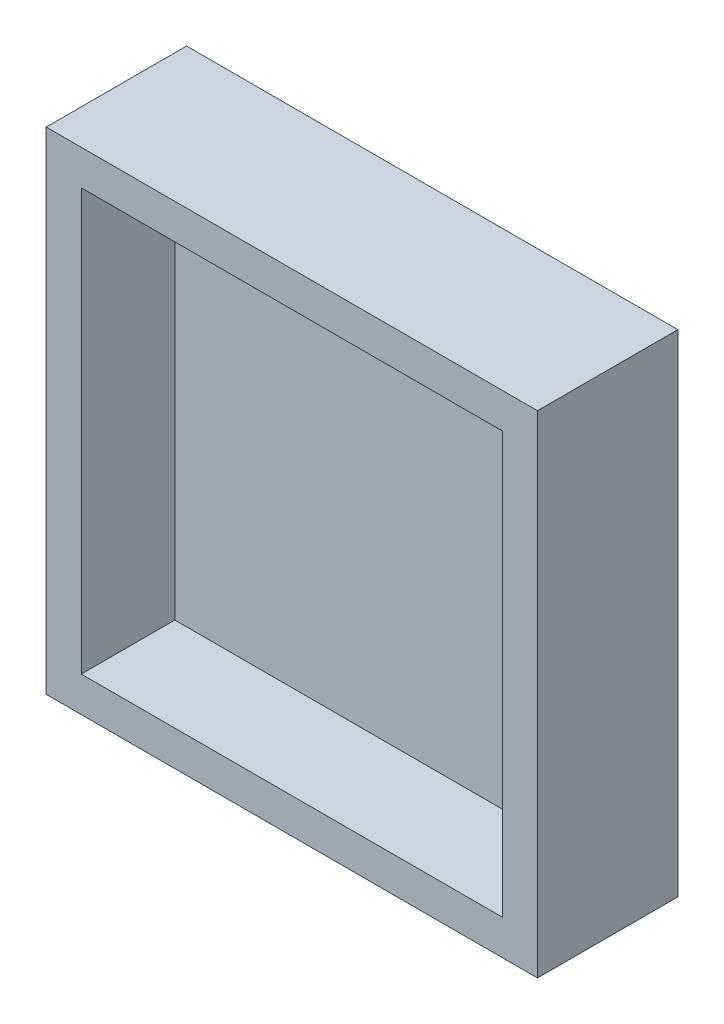
SolidWorks part; units mm, degrees
ref_plane "Front Plane" through (0, 0, 0) normal (0, 0, 1) x (1, 0, 0)
ref_plane "Top Plane" through (0, 0, 0) normal (0, 1, 0) x (1, 0, 0)
ref_plane "Right Plane" through (0, 0, 0) normal (1, 0, 0) x (0, 0, -1)
sketch "Sketch1" plane through (0, 0, 0) normal (0, 0, 1) x (1, 0, 0)
  line L1 (-66.675, -66.675) -> (66.675, -66.675)
  line L2 (-66.675, -66.675) -> (-66.675, 66.675)
  line L3 (-66.675, 66.675) -> (66.675, 66.675)
  line L4 (66.675, -66.675) -> (66.675, 66.675)
  line L5 (-66.675, -66.675) -> (66.675, 66.675) construction
  line L6 (-66.675, 66.675) -> (66.675, -66.675) construction
  point P0 (0, 0)
  dimension "D1" = 133.35
  dimension "D2" = 133.35
extrude "Boss-Extrude1" add sketch "Sketch1" along normal blind 38.1 contours L2 L1 L4 L3
sketch "Sketch2" plane through (0, 0, 38.1) normal (0, 0, 1) x (1, 0, 0)
  line L1 (-57.15, -57.15) -> (57.15, -57.15)
  line L2 (-57.15, -57.15) -> (-57.15, 57.15)
  line L3 (-57.15, 57.15) -> (57.15, 57.15)
  line L4 (57.15, -57.15) -> (57.15, 57.15)
  line L5 (-57.15, -57.15) -> (57.15, 57.15) construction
  line L6 (-57.15, 57.15) -> (57.15, -57.15) construction
  point P0 (0, 0)
  dimension "D1" = 114.3
  dimension "D2" = 114.3
extrude "Cut-Extrude1" cut sketch "Sketch2" against normal blind 25.4
